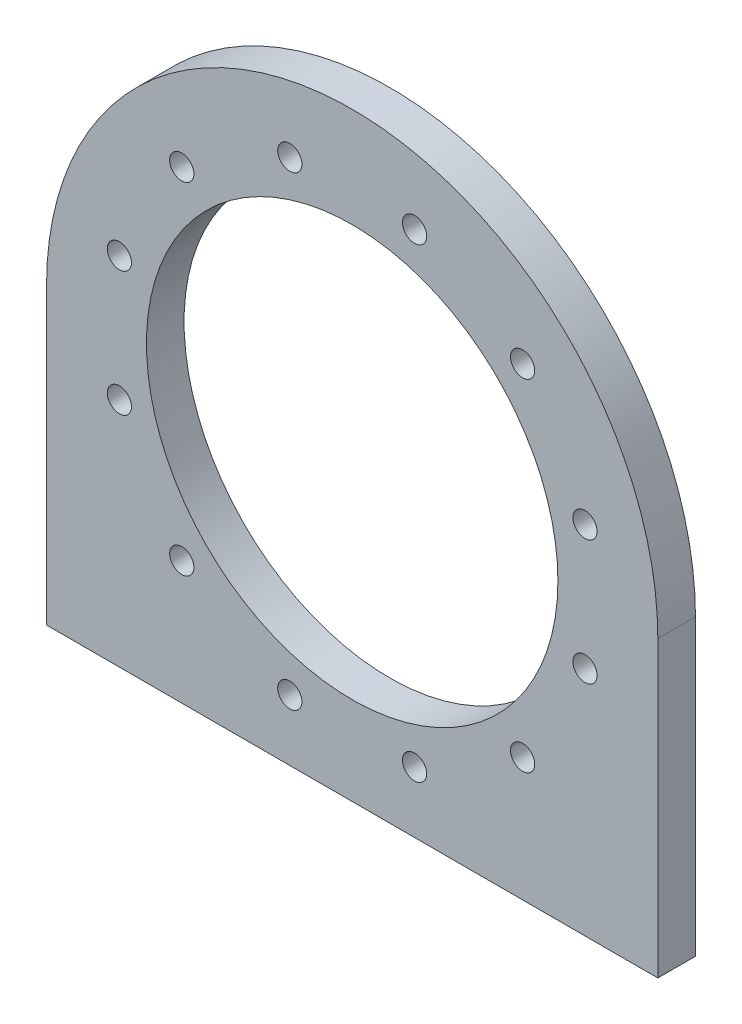
SolidWorks part; units mm, degrees
ref_plane "前视基准面" through (0, 0, 0) normal (0, 0, 1) x (1, 0, 0)
ref_plane "上视基准面" through (0, 0, 0) normal (0, 1, 0) x (1, 0, 0)
ref_plane "右视基准面" through (0, 0, 0) normal (1, 0, 0) x (0, 0, -1)
sketch "草图1" plane through (0, 0, 0) normal (0, 0, 1) x (1, 0, 0)
  line L0 (-130, 0) -> (-130, -125)
  line L1 (-130, -125) -> (130, -125)
  line L2 (130, -125) -> (130, 0)
  circle A0 centre (0, 0) radius 87.5
  arc A1 (130, 0) -> (-130, 0) centre (0, 0) ccw
  dimension "D1" = 175
  dimension "D2" = 260
  dimension "D3" = 125
extrude "凸台-拉伸1" add sketch "草图1" along normal blind 16
sketch "草图2" plane through (0, 0, 16) normal (0, 0, 1) x (1, 0, 0)
  line L0 (0, 0) -> (-26.529, 99.0074) construction
  line L1 (0, 0) -> (0, 190.6578) construction
  circle A0 centre (0, 0) radius 102.5 construction
  circle A1 centre (-26.529, 99.0074) radius 5.15
  circle A2 centre (26.529, 99.0074) radius 5.15
  circle A3 centre (72.4784, 72.4784) radius 5.15
  circle A4 centre (99.0074, 26.529) radius 5.15
  circle A5 centre (99.0074, -26.529) radius 5.15
  circle A6 centre (72.4784, -72.4784) radius 5.15
  circle A7 centre (26.529, -99.0074) radius 5.15
  circle A8 centre (-26.529, -99.0074) radius 5.15
  circle A9 centre (-72.4784, -72.4784) radius 5.15
  circle A10 centre (-99.0074, -26.529) radius 5.15
  circle A11 centre (-99.0074, 26.529) radius 5.15
  circle A12 centre (-72.4784, 72.4784) radius 5.15
  dimension "D1" = 205
  dimension "D2" = 10.3
  dimension "D4" = 102.5
  dimension "D5" = 15
  dimension "D3" = 12
extrude "切除-拉伸1" cut sketch "草图2" against normal up to next
